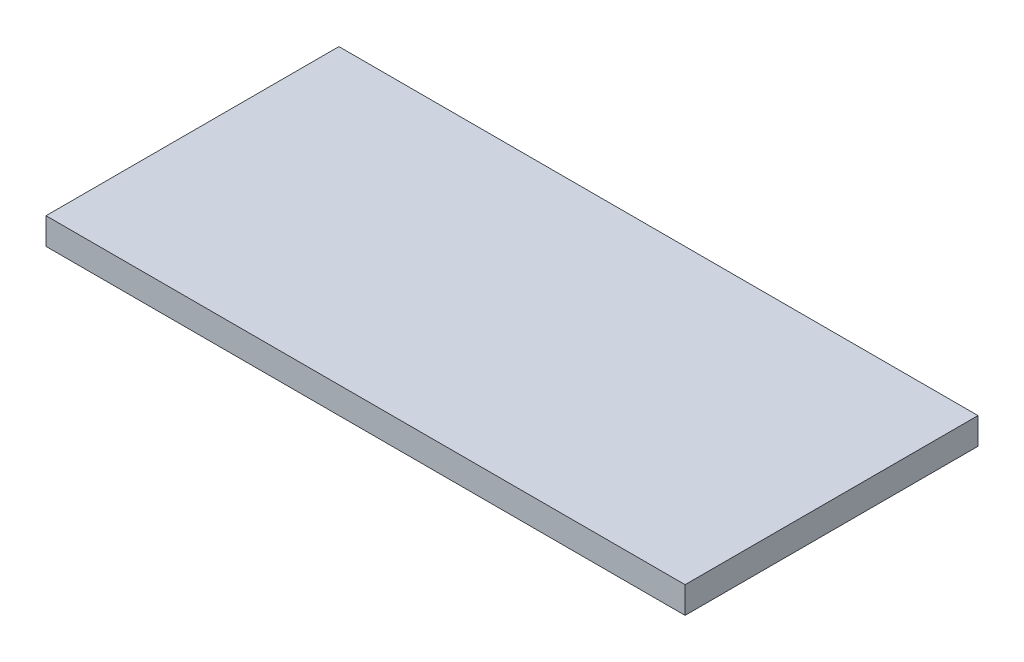
SolidWorks part; units mm, degrees
ref_plane "Alzado" through (0, 0, 0) normal (0, 0, 1) x (1, 0, 0)
ref_plane "Planta" through (0, 0, 0) normal (0, 1, 0) x (1, 0, 0)
ref_plane "Vista lateral" through (0, 0, 0) normal (1, 0, 0) x (0, 0, -1)
sketch "Croquis1" plane through (0, 0, 0) normal (0, 1, 0) x (1, 0, 0)
  line L1 (-600, 275) -> (600, 275)
  line L2 (-600, 275) -> (-600, -275)
  line L3 (-600, -275) -> (600, -275)
  line L4 (600, 275) -> (600, -275)
  line L5 (-600, 275) -> (600, -275) construction
  line L6 (-600, -275) -> (600, 275) construction
  point P0 (0, 0)
  dimension "D1" = 1200
  dimension "D2" = 550
extrude "Saliente-Extruir1" add sketch "Croquis1" along normal blind 50
